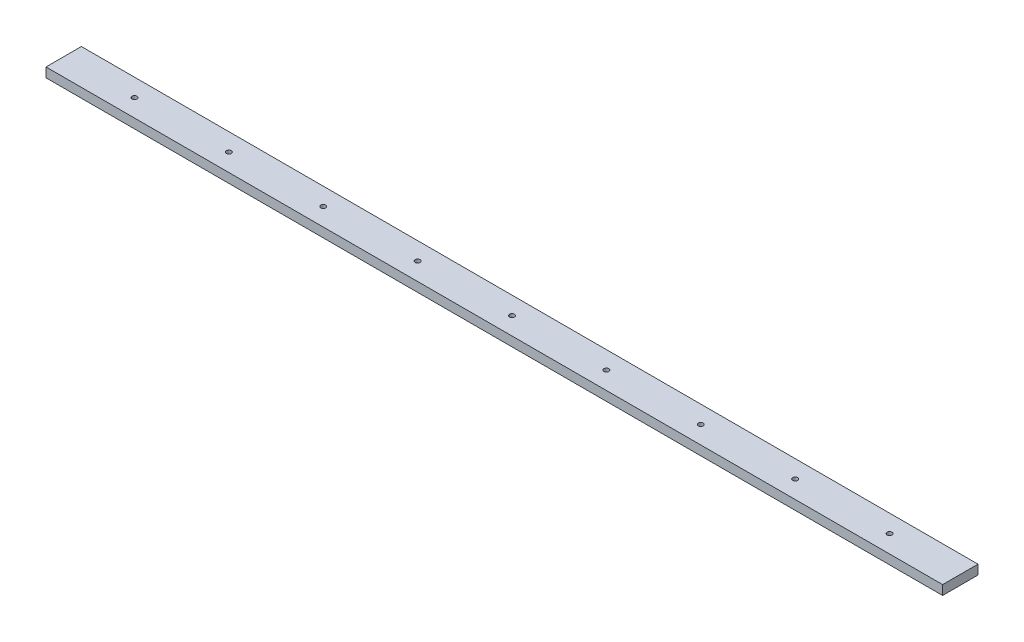
SolidWorks part; units mm, degrees
ref_plane "Front Plane" through (0, 0, 0) normal (0, 0, 1) x (1, 0, 0)
ref_plane "Top Plane" through (0, 0, 0) normal (0, 1, 0) x (1, 0, 0)
ref_plane "Right Plane" through (0, 0, 0) normal (1, 0, 0) x (0, 0, -1)
sketch "Sketch1" plane through (0, 0, 0) normal (0, 1, 0) x (1, 0, 0)
  line L1 (-380, 15) -> (380, 15)
  line L2 (-380, 15) -> (-380, -15)
  line L3 (-380, -15) -> (380, -15)
  line L4 (380, 15) -> (380, -15)
  line L5 (-380, 15) -> (380, -15) construction
  line L6 (-380, -15) -> (380, 15) construction
  point P0 (0, 0)
  dimension "D1" = 760
  dimension "D2" = 30
extrude "Boss-Extrude1" add sketch "Sketch1" along normal blind 8
hole_wizard "M5 Tapped Hole1" positions "Sketch3" profile "Sketch4" tap size "M5" standard "ISO" end condition through all
sketch "Sketch3" plane through (0, 8, 0) normal (0, 1, 0) x (1, 0, 0)
  point P0 (0, 0)
  point P10 (80, 0)
  point P11 (160, 0)
  point P12 (240, 0)
  point P13 (320, 0)
  point P20 (-80, 0)
  point P21 (-160, 0)
  point P22 (-240, 0)
  point P23 (-320, 0)
  dimension "D1" = 5
  dimension "D2" = 5
sketch "Sketch4" plane through (0, 8, 0) normal (1, 0, 0) x (0, 0, 1)
  line L0 (0, 0) -> (0, 8)
  line L1 (0, 8) -> (2.1, 8)
  line L2 (2.1, 8) -> (2.1, 0)
  line L5 (2.1, 0) -> (0, 0)
  line L11 (0, -6.35) -> (0, 107.95) construction
  dimension "Thru Tap Drill Dia." = 4.2
  dimension "Thru Tap Drill Depth" = 8
cosmetic thread "Hole Thread1"
cosmetic thread "Hole Thread2"
cosmetic thread "Hole Thread3"
cosmetic thread "Hole Thread4"
cosmetic thread "Hole Thread5"
cosmetic thread "Hole Thread6"
cosmetic thread "Hole Thread7"
cosmetic thread "Hole Thread8"
cosmetic thread "Hole Thread9"
